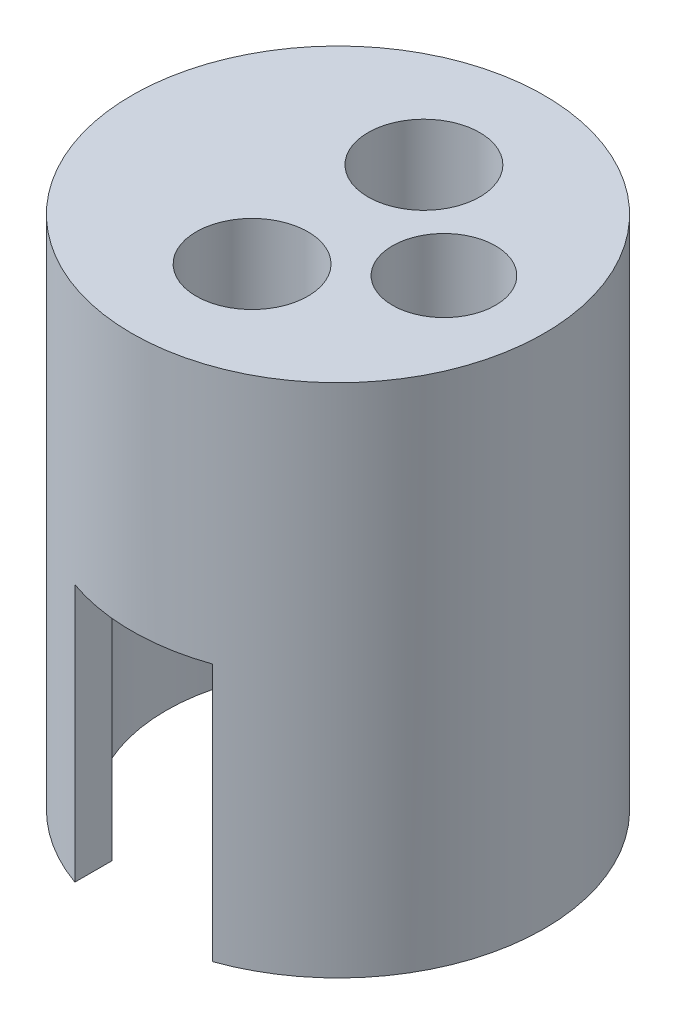
SolidWorks part; units mm, degrees
ref_plane "Front Plane" through (0, 0, 0) normal (0, 0, 1) x (1, 0, 0)
ref_plane "Top Plane" through (0, 0, 0) normal (0, 1, 0) x (1, 0, 0)
ref_plane "Right Plane" through (0, 0, 0) normal (1, 0, 0) x (0, 0, -1)
sketch "Sketch1" plane through (0, 0, 0) normal (0, 1, 0) x (1, 0, 0)
  line L0 (13.2652, 10.7486) -> (13.2652, 12.8972)
  line L1 (17.2652, 6.5835) -> (17.2652, 7.8335) construction
  line L2 (21.2652, 10.7486) -> (21.2652, 12.8972)
  line L3 (21.2652, -0.4913) -> (21.2652, 3.6582)
  line L7 (21.2652, -9.7303) -> (21.2652, -7.5817)
  line L8 (13.2652, -9.7303) -> (13.2652, -7.5817)
  circle A0 centre (17.2652, 6.5835) radius 1.25
  circle A1 centre (17.2652, -3.4165) radius 1.25
  arc A2 (13.2652, 10.7486) -> (13.2652, -7.5817) centre (17.2652, 1.5835) ccw
  circle A3 centre (23.4321, 1.5835) radius 3
  circle A4 centre (17.2652, 1.5835) radius 12
  arc A5 (21.2652, -7.5817) -> (21.2652, 10.7486) centre (17.2652, 1.5835) ccw
  circle A6 centre (17.2652, 1.5835) radius 10 construction
  point P7 (26.8282, 4.5072)
  dimension "D1" = 2.5
  dimension "D2" = 2.5
  dimension "D4" = 6
  dimension "D5" = 2
extrude "Boss-Extrude1" add sketch "Sketch1" along normal blind 15 contours L7 A5 L2 A4 L0 A2 L8 A0 A1 A3 | L0 A4 L8 A2 | A5 L7 A4 L2
sketch "Sketch3" plane through (0, 0, 0) normal (0, -1, 0) x (1, 0, 0)
  line L0 (13.2652, -10.7486) -> (13.2652, -12.8972)
  line L1 (13.2652, 9.7303) -> (13.2652, 7.5817)
  line L2 (21.2652, 9.7303) -> (21.2652, 7.5817)
  line L3 (21.2652, -10.7486) -> (21.2652, -12.8972)
  circle A0 centre (17.2652, -1.5835) radius 12
  arc A1 (21.2652, -10.7486) -> (21.2652, 7.5817) centre (17.2652, -1.5835) ccw
  arc A3 (13.2652, 7.5817) -> (13.2652, -10.7486) centre (17.2652, -1.5835) ccw
  circle A4 centre (17.2652, -1.5835) radius 10 construction
  point P5 (17.2652, 11.3253)
  point P6 (17.2652, -14.9969)
  point P7 (13.2652, 11.3253)
  point P8 (13.2652, -14.9969)
  point P9 (21.2652, 11.3253)
  point P10 (21.2652, -14.9969)
  point P11 (27.2652, -1.5835)
  circle M2 centre (17.2652, -1.5835) radius 12
  dimension "D1" = 2
extrude "Boss-Extrude2" add sketch "Sketch3" along normal blind 15 contours A3 L1 L0 M2 | A1 L3 L2 M2
sketch "Sketch4" plane through (0, 0, 0) normal (0, -1, 0) x (1, 0, 0)
  circle A2 centre (17.2652, -6.5835) radius 2.25
  circle A3 centre (17.2652, -6.5835) radius 2.25
  dimension "D1" = 1
extrude "Cut-Extrude2" cut sketch "Sketch4" against normal blind 2.5
sketch "Sketch5" plane through (0, 0, 0) normal (0, -1, 0) x (1, 0, 0)
  circle A2 centre (17.2652, 3.4165) radius 2.25
  circle A3 centre (17.2652, 3.4165) radius 2.25
  dimension "D1" = 1
extrude "Cut-Extrude3" cut sketch "Sketch5" against normal blind 2.5
sketch "Sketch6" plane through (0, 0, 0) normal (0, -1, 0) x (1, 0, 0)
  circle A6 centre (23.4321, -1.5835) radius 3.7
  circle A7 centre (23.4321, -1.5835) radius 3.7
  dimension "D1" = 0.7
extrude "Cut-Extrude4" cut sketch "Sketch6" against normal blind 2
sketch "Sketch12" plane through (0, 15, 0) normal (0, 1, 0) x (1, 0, 0)
  circle A2 centre (17.2652, 6.5835) radius 3.25
  circle A3 centre (17.2652, 6.5835) radius 3.25
  dimension "D1" = 2
extrude "Cut-Extrude5" cut sketch "Sketch12" against normal blind 7
sketch "Sketch13" plane through (0, 15, 0) normal (0, 1, 0) x (1, 0, 0)
  circle A3 centre (17.2652, -3.4165) radius 3.25
  circle A4 centre (17.2652, -3.4165) radius 3.25
  dimension "D1" = 2
extrude "Cut-Extrude6" cut sketch "Sketch13" against normal blind 7
